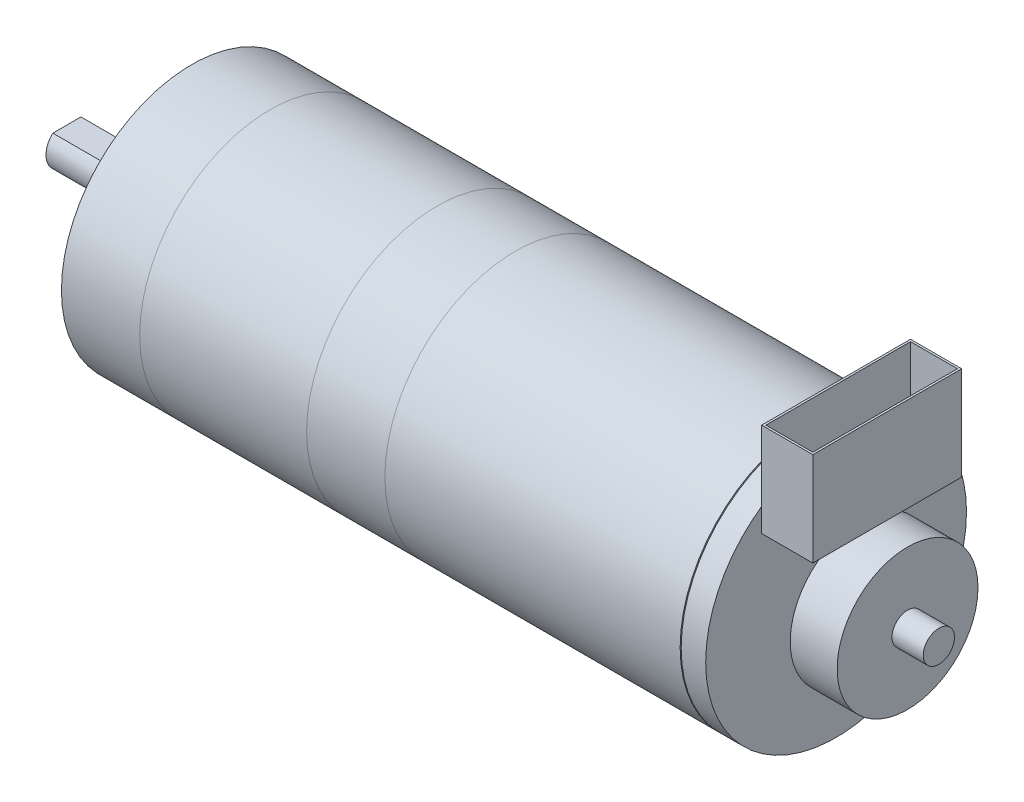
SolidWorks part; units mm, degrees
ref_plane "前视基准面" through (0, 0, 0) normal (0, 0, 1) x (1, 0, 0)
ref_plane "上视基准面" through (0, 0, 0) normal (0, 1, 0) x (1, 0, 0)
ref_plane "右视基准面" through (0, 0, 0) normal (1, 0, 0) x (0, 0, -1)
other "Configuration Table"
sketch "草图1" plane through (0, 0, 0) normal (1, 0, 0) x (0, 0, -1)
  circle A0 centre (0, 0) radius 12.5
  dimension "D1" = 25
extrude "凸台-拉伸1" add sketch "草图1" along normal blind 7.5
sketch "草图3" plane through (7.5, 0, 0) normal (1, 0, 0) x (0, 0, -1)
  circle A0 centre (0, 0) radius 12.5
  dimension "D1" = 25
extrude "凸台-拉伸3" add sketch "草图3" along normal blind 16 separate body
sketch "草图4" plane through (23.5, 0, 0) normal (1, 0, 0) x (0, 0, -1)
  circle A0 centre (0, 0) radius 12.5
  dimension "D1" = 25
extrude "凸台-拉伸4" add sketch "草图4" along normal blind 7.5 separate body
sketch "草图5" plane through (31, 0, 0) normal (1, 0, 0) x (0, 0, -1)
  circle A0 centre (0, 0) radius 12.5
  dimension "D1" = 25
extrude "凸台-拉伸5" add sketch "草图5" along normal blind 28.3 separate body
sketch "草图6" plane through (59.3, 0, 0) normal (1, 0, 0) x (0, 0, -1)
  circle A0 centre (0, 0) radius 1.5
  dimension "D1" = 3
extrude "凸台-拉伸10" add sketch "草图6" along normal blind 0.1
sketch "草图10" plane through (59.4, 0, 0) normal (1, 0, 0) x (0, 0, -1)
  circle A0 centre (0, 0) radius 12.5
extrude "凸台-拉伸11" add sketch "草图10" along normal blind 2.35
sketch "草图12" plane through (61.75, 0, 0) normal (1, 0, 0) x (0, 0, -1)
  circle A0 centre (0, 0) radius 1.5
  dimension "D1" = 3
extrude "凸台-拉伸12" add sketch "草图12" along normal blind 2.35
sketch "草图13" plane through (64.1, 0, 0) normal (1, 0, 0) x (0, 0, -1)
  circle A0 centre (0, 0) radius 6.75
  dimension "D1" = 13.5
extrude "凸台-拉伸13" add sketch "草图13" along normal blind 4.5
sketch "草图14" plane through (68.6, 0, 0) normal (1, 0, 0) x (0, 0, -1)
  circle A0 centre (0, 0) radius 1.5
  dimension "D1" = 3
extrude "凸台-拉伸14" add sketch "草图14" along normal blind 3
sketch "草图15" plane through (0, 0, 0) normal (0, 1, 0) x (1, 0, 0)
  line L0 (0, 0) -> (83.7426, 0) construction
  line L1 (61.95, -6.93) -> (61.95, 6.93)
  line L2 (61.95, 6.93) -> (66.45, 6.93)
  line L3 (66.45, 6.93) -> (66.45, -6.93)
  line L4 (61.75, -12.5) -> (61.75, 12.5) construction
  line L5 (61.95, -6.93) -> (66.45, -6.93)
  point P10 (66.45, 0)
  point P11 (61.95, 0)
  dimension "D1" = 6.93
  dimension "D2" = 4.5
  dimension "D3" = 0.2
extrude "拉伸-薄壁1" add sketch "草图15" along normal blind 9 from offset 8 separate body thin thin type one direction wall 0.2
sketch "草图16" plane through (0, 0, 0) normal (-1, 0, 0) x (0, 0, 1)
  circle A0 centre (0, 0) radius 3.5
  dimension "D1" = 7
extrude "凸台-拉伸15" add sketch "草图16" along normal blind 2.38
sketch "草图17" plane through (-2.38, 0, 0) normal (-1, 0, 0) x (0, 0, 1)
  circle A0 centre (0, 0) radius 2
  dimension "D1" = 4
extrude "凸台-拉伸16" add sketch "草图17" along normal blind 9.6
sketch "草图18" plane through (-11.98, 0, 0) normal (-1, 0, 0) x (0, 0, 1)
  line L0 (0, 0) -> (0, 2) construction
  line L1 (0, 1.48) -> (1.3452, 1.48) construction
  line L2 (0, 1.48) -> (-1.3452, 1.48) construction
  line L3 (-1.3452, 1.48) -> (-1.3452, 2.2351)
  line L4 (-1.3452, 2.2351) -> (1.3452, 2.2351)
  line L5 (1.3452, 2.2351) -> (1.3452, 1.48)
  line L6 (-1.3452, 1.48) -> (1.3452, 1.48)
  circle A0 centre (0, 0) radius 2 construction
  dimension "D1" = 1.48
extrude "切除-拉伸1" cut sketch "草图18" against normal blind 8
sketch "草图19" plane through (0, 0, 0) normal (-1, 0, 0) x (0, 0, 1)
  line L0 (0, 0) -> (16.9005, 0) construction
  circle A0 centre (8.5, 0) radius 1.75
  dimension "D1" = 3.5
  dimension "D2" = 8.5
extrude "切除-拉伸2" cut sketch "草图19" against normal blind 3.5
mirror "镜向1" about plane through (0, 0, 0) normal (0, 0, 1) of "切除-拉伸2"
